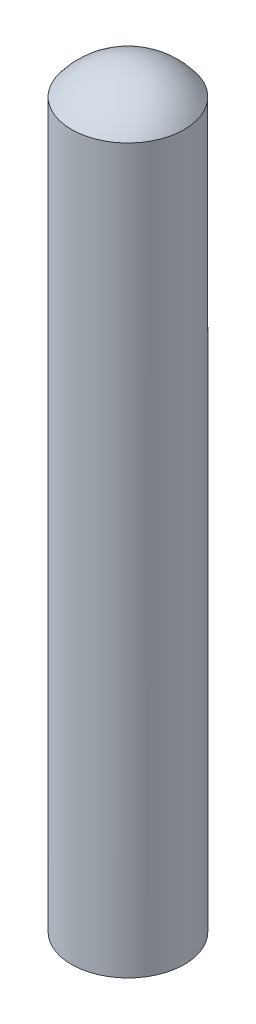
SolidWorks part; units mm, degrees
ref_plane "Front Plane" through (0, 0, 0) normal (0, 0, 1) x (1, 0, 0)
ref_plane "Top Plane" through (0, 0, 0) normal (0, 1, 0) x (1, 0, 0)
ref_plane "Right Plane" through (0, 0, 0) normal (1, 0, 0) x (0, 0, -1)
sketch "Sketch1" plane through (0, 0, 0) normal (0, 0, 1) x (1, 0, 0)
  line L3 (3, 38.4) -> (3, 0)
  line L4 (0, 39.9) -> (0, 0)
  line L5 (3, 0) -> (0, 0)
  arc A0 (3, 38.4) -> (0, 39.9) centre (0, 36.15) ccw
  point P4 (0, 0)
  point P10 (0, 39.9)
revolve "Revolve1" add sketch "Sketch1" angle 360 about L4
